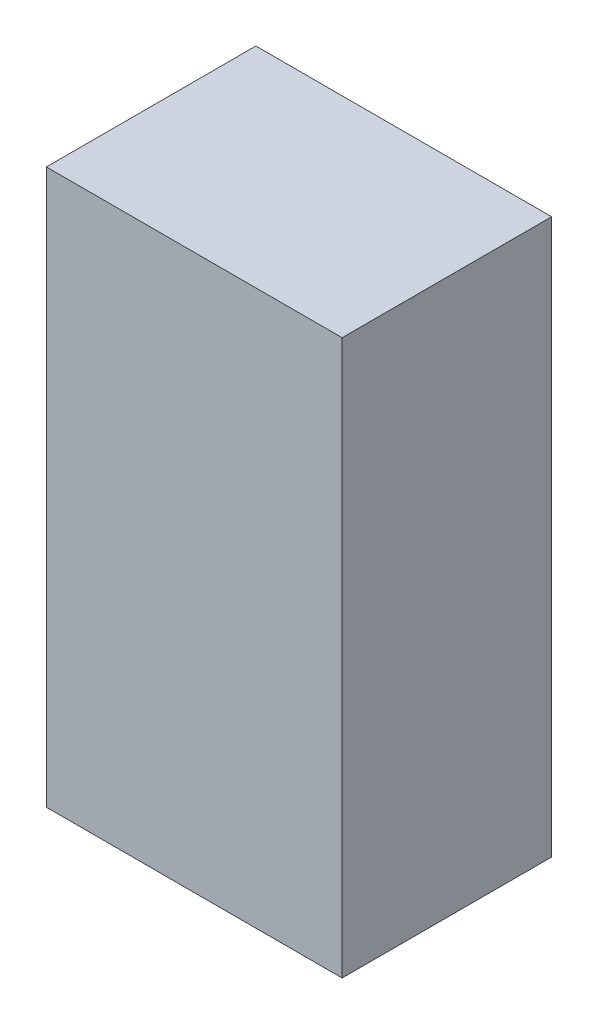
SolidWorks part; units mm, degrees
ref_plane "Front Plane" through (0, 0, 0) normal (0, 0, 1) x (1, 0, 0)
ref_plane "Top Plane" through (0, 0, 0) normal (0, 1, 0) x (1, 0, 0)
ref_plane "Right Plane" through (0, 0, 0) normal (1, 0, 0) x (0, 0, -1)
sketch "Sketch1" plane through (0, 0, 0) normal (0, 0, 1) x (1, 0, 0)
  line L1 (60, -112.5) -> (-60, -112.5)
  line L2 (60, -112.5) -> (60, 112.5)
  line L3 (60, 112.5) -> (-60, 112.5)
  line L4 (-60, -112.5) -> (-60, 112.5)
  line L5 (60, -112.5) -> (-60, 112.5) construction
  line L6 (60, 112.5) -> (-60, -112.5) construction
  point P0 (0, 0)
  dimension "D1" = 120
  dimension "D2" = 225
extrude "Boss-Extrude1" add sketch "Sketch1" along normal blind 85
